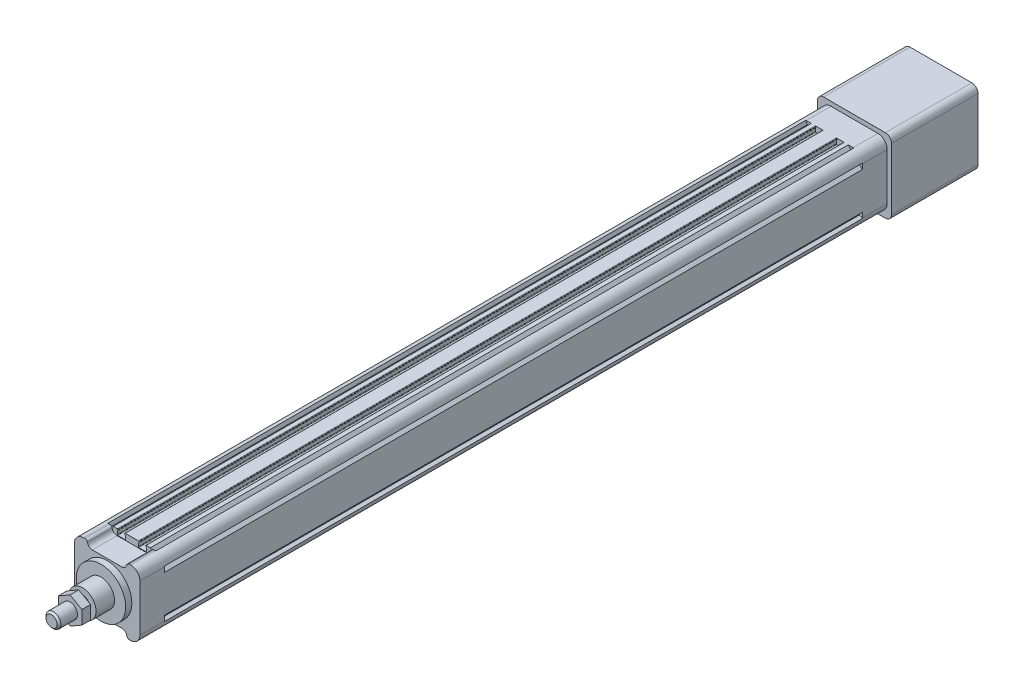
SolidWorks part; units mm, degrees
ref_plane "Front" through (0, 0, 0) normal (0, 0, 1) x (1, 0, 0)
ref_plane "Top" through (0, 0, 0) normal (0, 1, 0) x (1, 0, 0)
ref_plane "Right" through (0, 0, 0) normal (1, 0, 0) x (0, 0, -1)
sketch "草图1" plane through (0, 0, 0) normal (0, 0, 1) x (1, 0, 0)
  line L0 (19.7737, 3) -> (23.3, 3)
  line L1 (23.3, 3) -> (23.3, -3)
  line L2 (23.3, -3) -> (19.7737, -3)
  line L3 (-19.7737, -3) -> (-23.3, -3)
  line L4 (-23.3, -3) -> (-23.3, 3)
  line L5 (-23.3, 3) -> (-19.7737, 3)
  line L6 (-18.2, 24) -> (-19.4434, 26.4869)
  line L7 (-26.4869, 19.4434) -> (-24, 18.2)
  line L8 (-24, 18.2) -> (-24, 17.1)
  line L9 (-24, 17.1) -> (-26.5, 15)
  line L10 (-26.5, 15) -> (-26.5, -15)
  line L11 (-26.5, -15) -> (-24, -17.1)
  line L12 (-24, -17.1) -> (-24, -18.2)
  line L13 (-24, -18.2) -> (-26.4869, -19.4434)
  line L14 (-19.4434, -26.4869) -> (-18.2, -24)
  line L15 (-18.2, -24) -> (-17.1, -24)
  line L16 (-17.1, -24) -> (-15, -26.5)
  line L17 (-15, -26.5) -> (-11.65, -26.5)
  line L18 (-11.25, -26.1) -> (-11.25, -25.6)
  line L19 (-11.65, -25.2) -> (-11.75, -25.2)
  line L20 (-11.75, -25.2) -> (-11.75, -22.4)
  line L21 (-11.35, -22) -> (-5.65, -22)
  line L22 (-5.25, -22.4) -> (-5.25, -25.2)
  line L23 (-5.25, -25.2) -> (-5.35, -25.2)
  line L24 (-5.75, -25.6) -> (-5.75, -26.1)
  line L25 (-5.35, -26.5) -> (5.35, -26.5)
  line L26 (5.75, -26.1) -> (5.75, -25.6)
  line L27 (5.35, -25.2) -> (5.25, -25.2)
  line L28 (5.25, -25.2) -> (5.25, -22.4)
  line L29 (5.65, -22) -> (11.35, -22)
  line L30 (11.75, -22.4) -> (11.75, -25.2)
  line L31 (11.75, -25.2) -> (11.65, -25.2)
  line L32 (11.25, -25.6) -> (11.25, -26.1)
  line L33 (11.65, -26.5) -> (15, -26.5)
  line L34 (15, -26.5) -> (17.1, -24)
  line L35 (17.1, -24) -> (18.2, -24)
  line L36 (18.2, -24) -> (19.4434, -26.4869)
  line L37 (26.4869, -19.4434) -> (24, -18.2)
  line L38 (24, -18.2) -> (24, -17.1)
  line L39 (24, -17.1) -> (26.5, -15)
  line L40 (26.5, -15) -> (26.5, 15)
  line L41 (26.5, 15) -> (24, 17.1)
  line L42 (24, 17.1) -> (24, 18.2)
  line L43 (24, 18.2) -> (26.4869, 19.4434)
  line L44 (19.4434, 26.4869) -> (18.2, 24)
  line L45 (18.2, 24) -> (17.1, 24)
  line L46 (17.1, 24) -> (15, 26.5)
  line L47 (15, 26.5) -> (11.65, 26.5)
  line L48 (11.25, 26.1) -> (11.25, 25.6)
  line L49 (11.65, 25.2) -> (11.75, 25.2)
  line L50 (11.75, 25.2) -> (11.75, 22.4)
  line L51 (11.35, 22) -> (5.65, 22)
  line L52 (5.25, 22.4) -> (5.25, 25.2)
  line L53 (5.25, 25.2) -> (5.35, 25.2)
  line L54 (5.75, 25.6) -> (5.75, 26.1)
  line L55 (5.35, 26.5) -> (-5.35, 26.5)
  line L56 (-5.75, 26.1) -> (-5.75, 25.6)
  line L57 (-5.35, 25.2) -> (-5.25, 25.2)
  line L58 (-5.25, 25.2) -> (-5.25, 22.4)
  line L59 (-5.65, 22) -> (-11.35, 22)
  line L60 (-11.75, 22.4) -> (-11.75, 25.2)
  line L61 (-11.75, 25.2) -> (-11.65, 25.2)
  line L62 (-11.25, 25.6) -> (-11.25, 26.1)
  line L63 (-11.65, 26.5) -> (-15, 26.5)
  line L64 (-15, 26.5) -> (-17.1, 24)
  line L65 (-17.1, 24) -> (-18.2, 24)
  arc A0 (19.7737, 3) -> (-19.7737, 3) centre (0, 0) ccw
  arc A1 (-19.7737, -3) -> (19.7737, -3) centre (0, 0) ccw
  circle A2 centre (19, 19) radius 2.1
  circle A3 centre (19, -19) radius 2.1
  circle A4 centre (-19, -19) radius 2.1
  circle A5 centre (-19, 19) radius 2.1
  arc A6 (-19.4434, 26.4869) -> (-26.4869, 19.4434) centre (-19, 19) ccw
  arc A7 (-26.4869, -19.4434) -> (-19.4434, -26.4869) centre (-19, -19) ccw
  arc A8 (-11.65, -26.5) -> (-11.25, -26.1) centre (-11.65, -26.1) ccw
  arc A9 (-11.25, -25.6) -> (-11.65, -25.2) centre (-11.65, -25.6) ccw
  arc A10 (-11.35, -22) -> (-11.75, -22.4) centre (-11.35, -22.4) ccw
  arc A11 (-5.25, -22.4) -> (-5.65, -22) centre (-5.65, -22.4) ccw
  arc A12 (-5.35, -25.2) -> (-5.75, -25.6) centre (-5.35, -25.6) ccw
  arc A13 (-5.75, -26.1) -> (-5.35, -26.5) centre (-5.35, -26.1) ccw
  arc A14 (5.35, -26.5) -> (5.75, -26.1) centre (5.35, -26.1) ccw
  arc A15 (5.75, -25.6) -> (5.35, -25.2) centre (5.35, -25.6) ccw
  arc A16 (5.65, -22) -> (5.25, -22.4) centre (5.65, -22.4) ccw
  arc A17 (11.75, -22.4) -> (11.35, -22) centre (11.35, -22.4) ccw
  arc A18 (11.65, -25.2) -> (11.25, -25.6) centre (11.65, -25.6) ccw
  arc A19 (11.25, -26.1) -> (11.65, -26.5) centre (11.65, -26.1) ccw
  arc A20 (19.4434, -26.4869) -> (26.4869, -19.4434) centre (19, -19) ccw
  arc A21 (26.4869, 19.4434) -> (19.4434, 26.4869) centre (19, 19) ccw
  arc A22 (11.65, 26.5) -> (11.25, 26.1) centre (11.65, 26.1) ccw
  arc A23 (11.25, 25.6) -> (11.65, 25.2) centre (11.65, 25.6) ccw
  arc A24 (11.35, 22) -> (11.75, 22.4) centre (11.35, 22.4) ccw
  arc A25 (5.25, 22.4) -> (5.65, 22) centre (5.65, 22.4) ccw
  arc A26 (5.35, 25.2) -> (5.75, 25.6) centre (5.35, 25.6) ccw
  arc A27 (5.75, 26.1) -> (5.35, 26.5) centre (5.35, 26.1) ccw
  arc A28 (-5.35, 26.5) -> (-5.75, 26.1) centre (-5.35, 26.1) ccw
  arc A29 (-5.75, 25.6) -> (-5.35, 25.2) centre (-5.35, 25.6) ccw
  arc A30 (-5.65, 22) -> (-5.25, 22.4) centre (-5.65, 22.4) ccw
  arc A31 (-11.75, 22.4) -> (-11.35, 22) centre (-11.35, 22.4) ccw
  arc A32 (-11.65, 25.2) -> (-11.25, 25.6) centre (-11.65, 25.6) ccw
  arc A33 (-11.25, 26.1) -> (-11.65, 26.5) centre (-11.65, 26.1) ccw
extrude "凸台-拉伸1" add sketch "草图1" along normal blind 565
sketch "草图6" plane through (0, 0, 565) normal (0, 0, 1) x (1, 0, 0)
  line L0 (0, 0) -> (19, 0) construction
  line L2 (-26.5, -19) -> (-26.5, 19)
  line L3 (-19, 26.5) -> (-17.9161, 26.5)
  line L4 (26.5, -19) -> (26.5, 19)
  line L5 (-26.5, -26.5) -> (26.5, 26.5) construction
  line L6 (-26.5, 26.5) -> (26.5, -26.5) construction
  line L7 (-12, 21.5) -> (12, 21.5)
  line L9 (19, 26.5) -> (17.9161, 26.5)
  line L10 (19, -26.5) -> (17.9161, -26.5)
  line L11 (-12, -21.5) -> (12, -21.5)
  line L12 (-19, -26.5) -> (-17.9161, -26.5)
  arc A0 (12, 21.5) -> (15.9441, 24.8333) centre (12, 25.5) ccw
  arc A1 (-15.9441, 24.8333) -> (-12, 21.5) centre (-12, 25.5) ccw
  arc A2 (-15.9441, 24.8333) -> (-17.9161, 26.5) centre (-17.9161, 24.5) ccw
  arc A3 (15.9441, 24.8333) -> (17.9161, 26.5) centre (17.9161, 24.5) cw
  arc A4 (-26.5, -19) -> (-19, -26.5) centre (-19, -19) ccw
  arc A5 (19, -26.5) -> (26.5, -19) centre (19, -19) ccw
  arc A6 (26.5, 19) -> (19, 26.5) centre (19, 19) ccw
  arc A7 (-26.5, 19) -> (-19, 26.5) centre (-19, 19) cw
  arc A8 (15.9441, -24.8333) -> (17.9161, -26.5) centre (17.9161, -24.5) ccw
  arc A9 (12, -21.5) -> (15.9441, -24.8333) centre (12, -25.5) cw
  arc A10 (-15.9441, -24.8333) -> (-12, -21.5) centre (-12, -25.5) cw
  arc A11 (-15.9441, -24.8333) -> (-17.9161, -26.5) centre (-17.9161, -24.5) cw
  point P0 (0, 0)
  point P9 (0, 21.5)
  point P13 (20, 20.8461)
  point P16 (-12, 20.8461)
  dimension "D5" = 4
  dimension "D6" = 2
  dimension "D7" = 2
  dimension "D9" = 7.5
  dimension "D1" = 53
  dimension "D2" = 53
  dimension "D3" = 26.5
  dimension "D4" = 24
  dimension "D8" = 5
extrude "凸台-拉伸2" add sketch "草图6" along normal blind 20
sketch "草图7" plane through (0, 0, 585) normal (0, 0, 1) x (1, 0, 0)
  circle A0 centre (0, 0) radius 20
  dimension "D1" = 40
extrude "凸台-拉伸3" add sketch "草图7" along normal blind 5
sketch "草图9" plane through (0, 0, 590) normal (0, 0, 1) x (1, 0, 0)
  circle A0 centre (0, 0) radius 11
  dimension "D1" = 22
extrude "凸台-拉伸4" add sketch "草图9" along normal blind 15
sketch "草图10" plane through (0, 0, 605) normal (0, 0, 1) x (1, 0, 0)
  circle A0 centre (0, 0) radius 6
  dimension "D1" = 12
extrude "凸台-拉伸5" add sketch "草图10" along normal blind 25
sketch "草图11" plane through (0, 0, 0) normal (0, 0, -1) x (-1, 0, 0)
  line L1 (-19, -26.5) -> (19, -26.5)
  line L2 (-26.5, -19) -> (-26.5, 19)
  line L3 (-19, 26.5) -> (19, 26.5)
  line L4 (26.5, -19) -> (26.5, 19)
  line L5 (-26.5, -26.5) -> (26.5, 26.5) construction
  line L6 (-26.5, 26.5) -> (26.5, -26.5) construction
  arc A0 (-26.5, -19) -> (-19, -26.5) centre (-19, -19) ccw
  arc A1 (19, -26.5) -> (26.5, -19) centre (19, -19) ccw
  arc A2 (26.5, 19) -> (19, 26.5) centre (19, 19) ccw
  arc A3 (-26.5, 19) -> (-19, 26.5) centre (-19, 19) cw
  point P0 (0, 0)
  dimension "D3" = 7.5
  dimension "D1" = 53
  dimension "D2" = 53
extrude "凸台-拉伸6" add sketch "草图11" along normal blind 20
sketch "草图12" plane through (0, 0, -20) normal (0, 0, -1) x (-1, 0, 0)
  line L1 (-25, -30) -> (25, -30)
  line L2 (-30, -25) -> (-30, 25)
  line L3 (-25, 30) -> (25, 30)
  line L4 (30, -25) -> (30, 25)
  line L5 (-30, -30) -> (30, 30) construction
  line L6 (-30, 30) -> (30, -30) construction
  arc A0 (-30, -25) -> (-25, -30) centre (-25, -25) ccw
  arc A1 (25, -30) -> (30, -25) centre (25, -25) ccw
  arc A2 (30, 25) -> (25, 30) centre (25, 25) ccw
  arc A3 (-30, 25) -> (-25, 30) centre (-25, 25) cw
  point P0 (0, 0)
  dimension "D3" = 5
  dimension "D1" = 60
  dimension "D2" = 60
extrude "凸台-拉伸7" add sketch "草图12" along normal blind 70
sketch "草图14" plane through (0, 0, -90) normal (0, 0, -1) x (-1, 0, 0)
  circle A0 centre (0, 0) radius 19
  dimension "D1" = 38
extrude "切除-拉伸2" cut sketch "草图14" against normal blind 70
hole_wizard "M6 螺纹孔1" positions "草图15" profile "草图16" tap size "M6" standard "GB"
sketch "草图15" plane through (-26.5, 0, 0) normal (-1, 0, 0) x (0, 0, 1)
  line L0 (-20, -25) -> (-20, 25) construction
  line L1 (585, 19) -> (585, -19) construction
  point P0 (575, 11)
  point P2 (575, -11)
  point P4 (-10, 11)
  point P6 (-10, -11)
  dimension "D1" = 10
  dimension "D2" = 10
  dimension "D3" = 11
  dimension "D4" = 11
  dimension "D5" = 10
  dimension "D6" = 10
  dimension "D7" = 22
  dimension "D8" = 11
sketch "草图16" plane through (-26.5, 11, 575) normal (0, 1, 0) x (0, 0, 1)
  line L0 (0, 0) -> (0, 16.5022)
  line L1 (0, 16.5022) -> (2.5, 15)
  line L2 (2.5, 15) -> (2.5, 0)
  line L5 (2.5, 0) -> (0, 0)
  line L10 (0, 16.5022) -> (-2.5, 15) construction
  line L11 (0, -6.35) -> (0, 107.95) construction
  dimension "螺纹孔钻头直径" = 5
  dimension "螺纹孔钻头深度" = 15
  dimension "导头角度" = 118
cosmetic thread "孔螺蚊线4" parameters "D1"=12, "D2"=6
cosmetic thread "孔螺蚊线5" parameters "D1"=12, "D2"=6
cosmetic thread "孔螺蚊线6" parameters "D1"=12, "D2"=6
cosmetic thread "孔螺蚊线7" parameters "D1"=12, "D2"=6
chamfer "倒角1" distance 1.5 angle 45 1 edges at (6, 0, 630)
sketch "草图17" plane through (0, 0, 605) normal (0, 0, 1) x (1, 0, 0)
  line L1 (0, 10.9697) -> (-9.5, 5.4848)
  line L2 (-9.5, 5.4848) -> (-9.5, -5.4848)
  line L3 (-9.5, -5.4848) -> (0, -10.9697)
  line L4 (0, -10.9697) -> (9.5, -5.4848)
  line L5 (9.5, -5.4848) -> (9.5, 5.4848)
  line L6 (9.5, 5.4848) -> (0, 10.9697)
  circle A0 centre (0, 0) radius 9.5 construction
  dimension "D1" = 19
extrude "凸台-拉伸8" add sketch "草图17" along normal blind 7 from offset 3
